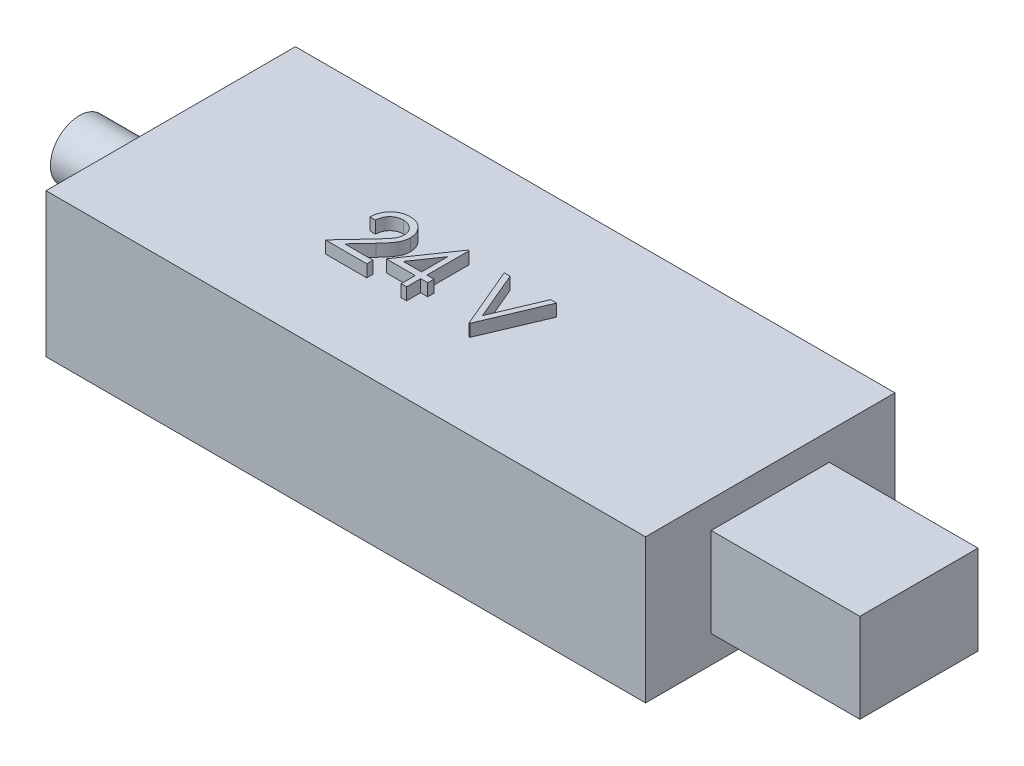
SolidWorks part; units mm, degrees
ref_plane "Front Plane" through (0, 0, 0) normal (0, 0, 1) x (1, 0, 0)
ref_plane "Top Plane" through (0, 0, 0) normal (0, 1, 0) x (1, 0, 0)
ref_plane "Right Plane" through (0, 0, 0) normal (1, 0, 0) x (0, 0, -1)
sketch "Sketch1" plane through (0, 0, 0) normal (0, 1, 0) x (1, 0, 0)
  line L1 (-62.5, 26) -> (62.5, 26)
  line L2 (-62.5, 26) -> (-62.5, -26)
  line L3 (-62.5, -26) -> (62.5, -26)
  line L4 (62.5, 26) -> (62.5, -26)
  line L5 (-62.5, 26) -> (62.5, -26) construction
  line L6 (-62.5, -26) -> (62.5, 26) construction
  point P0 (0, 0)
  dimension "D1" = 125
  dimension "D2" = 52
extrude "Boss-Extrude1" add sketch "Sketch1" along normal blind 30
sketch "Sketch2" plane through (62.5, 0, 0) normal (1, 0, 0) x (0, 0, -1)
  line L0 (-26, 15) -> (26, 15) construction
  line L1 (-26, 30) -> (-26, 0) construction
  line L2 (26, 30) -> (26, 0) construction
  line L4 (-12.3134, 24.2992) -> (12.3134, 24.2992)
  line L5 (-12.3134, 24.2992) -> (-12.3134, 5.7008)
  line L6 (-12.3134, 5.7008) -> (12.3134, 5.7008)
  line L7 (12.3134, 24.2992) -> (12.3134, 5.7008)
  line L8 (-12.3134, 24.2992) -> (12.3134, 5.7008) construction
  line L9 (-12.3134, 5.7008) -> (12.3134, 24.2992) construction
  point P6 (0, 15)
extrude "Boss-Extrude2" add sketch "Sketch2" along normal blind 31
sketch "Sketch3" plane through (-62.5, 0, 0) normal (-1, 0, 0) x (0, 0, 1)
  line L0 (-26, 15) -> (26, 15) construction
  line L1 (-26, 30) -> (-26, 0) construction
  line L2 (26, 30) -> (26, 0) construction
  circle A0 centre (0, 15) radius 6.0394
extrude "Boss-Extrude3" add sketch "Sketch3" along normal blind 19.05
sketch "Sketch4" plane through (0, 30, 0) normal (0, 1, 0) x (1, 0, 0)
  text T0 "24 V" font "Century Gothic" height 12.7
extrude "Boss-Extrude4" add sketch "Sketch4" along normal blind 2.54
